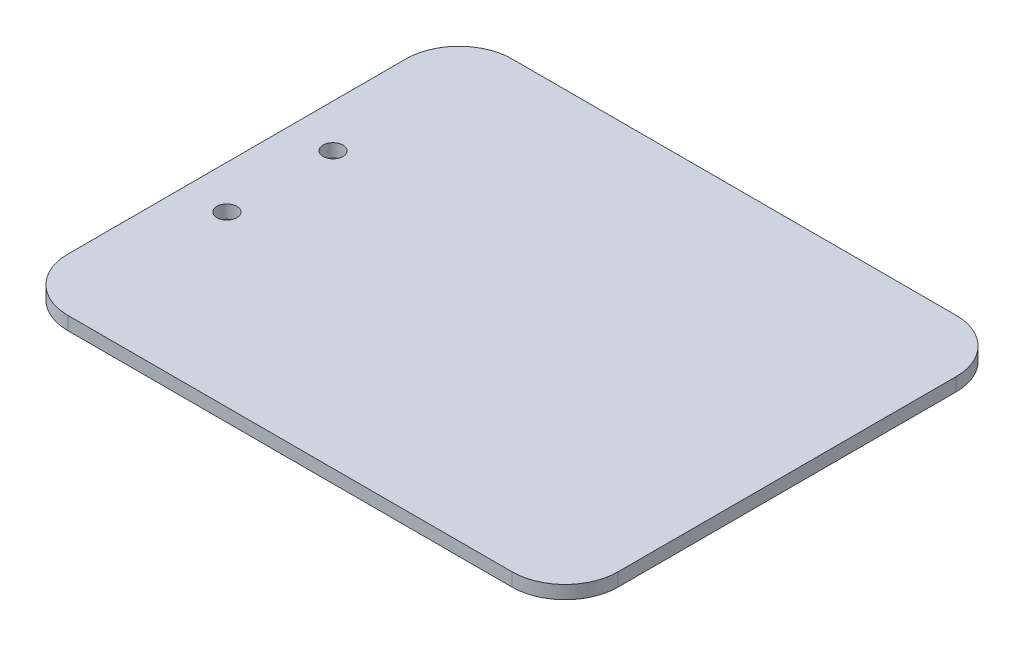
SolidWorks part; units mm, degrees
ref_plane "Front Plane" through (0, 0, 0) normal (0, 0, 1) x (1, 0, 0)
ref_plane "Top Plane" through (0, 0, 0) normal (0, 1, 0) x (1, 0, 0)
ref_plane "Right Plane" through (0, 0, 0) normal (1, 0, 0) x (0, 0, -1)
sketch "Sketch1" plane through (0, 0, 0) normal (0, 1, 0) x (1, 0, 0)
  line L0 (0, 33.5) -> (83, 33.5) construction
  line L1 (8, 0) -> (75, 0)
  line L2 (0, 8) -> (0, 59)
  line L3 (8, 67) -> (75, 67)
  line L4 (83, 8) -> (83, 59)
  line L5 (41.5, 67) -> (41.5, 0) construction
  circle A0 centre (6.5, 41.5) radius 1.5
  circle A1 centre (6.5, 25.5) radius 1.5
  arc A2 (8, 0) -> (0, 8) centre (8, 8) cw
  arc A3 (75, 0) -> (83, 8) centre (75, 8) ccw
  arc A4 (75, 67) -> (83, 59) centre (75, 59) cw
  arc A5 (0, 59) -> (8, 67) centre (8, 59) cw
  point P15 (0, 0)
  point P18 (83, 0)
  point P23 (0, 67)
  dimension "D3" = 3
  dimension "D6" = 8
  dimension "D1" = 83
  dimension "D2" = 67
  dimension "D4" = 6.5
  dimension "D5" = 8
extrude "Boss-Extrude1" add sketch "Sketch1" along normal blind 2
